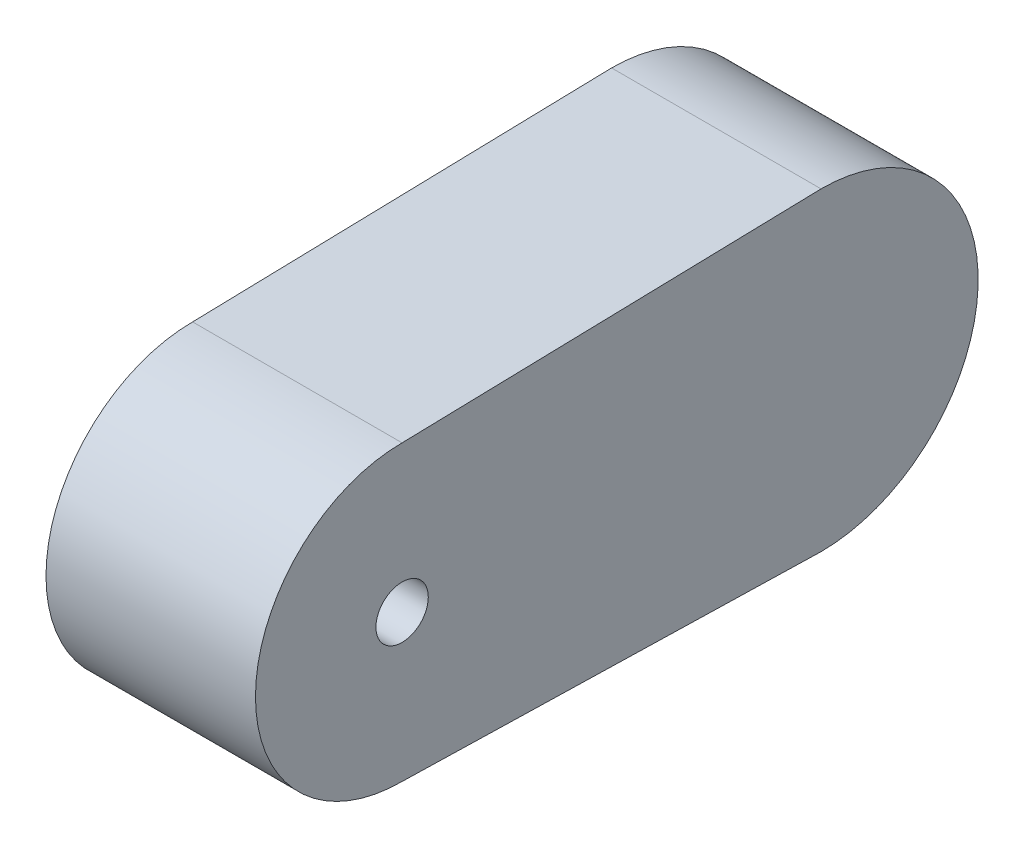
SolidWorks part; units mm, degrees
ref_plane "Alzado" through (0, 0, 0) normal (0, 0, 1) x (1, 0, 0)
ref_plane "Planta" through (0, 0, 0) normal (0, 1, 0) x (1, 0, 0)
ref_plane "Vista lateral" through (0, 0, 0) normal (1, 0, 0) x (0, 0, -1)
sketch "Croquis1" plane through (0, 0, 0) normal (1, 0, 0) x (0, 0, -1)
  line L0 (0, 0) -> (40, 0) construction
  line L1 (0, 14) -> (40, 15)
  line L2 (0, -14) -> (40, -15)
  arc A0 (0, 14) -> (0, -14) centre (0, 0) ccw
  arc A1 (40, -15) -> (40, 15) centre (40, 0) ccw
  circle A2 centre (0, 0) radius 2.5
  dimension "D2" = 28
  dimension "D3" = 30
  dimension "D4" = 5
  dimension "D1" = 40
extrude "Saliente-Extruir1" add sketch "Croquis1" along normal mid plane 20
